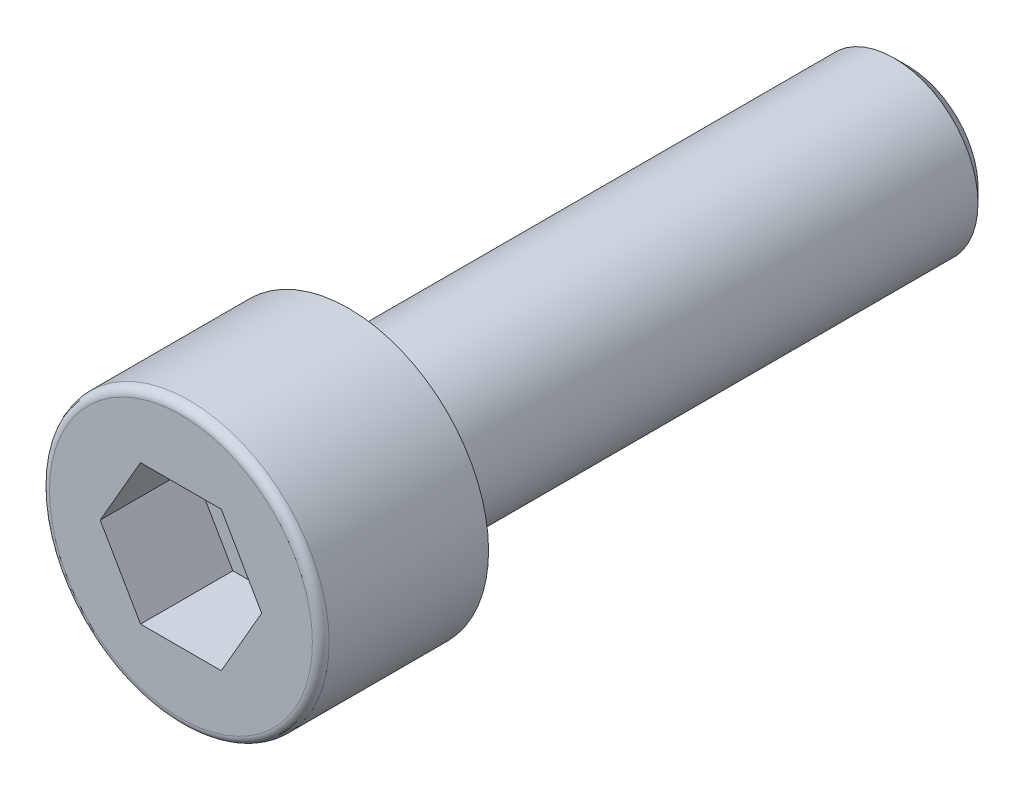
SolidWorks part; units mm, degrees
material "STAINLESS STEEL, 316S16"
ref_plane "Front Plane" through (0, 0, 0) normal (0, 0, 1) x (1, 0, 0)
ref_plane "Top Plane" through (0, 0, 0) normal (0, 1, 0) x (1, 0, 0)
ref_plane "Right Plane" through (0, 0, 0) normal (1, 0, 0) x (0, 0, -1)
sketch "Sketch1" plane through (0, 0, 0) normal (0, -1, 0) x (1, 0, 0)
  line L0 (0, 6) -> (0, -20) construction
  line L1 (0, -20) -> (-3, -20)
  line L2 (-3, -20) -> (-3, 0)
  line L3 (-3, 0) -> (-5, 0)
  line L4 (-5, 0) -> (-5, 5.7)
  line L5 (-4.7, 6) -> (0, 6)
  line L6 (0, 6) -> (0, -20)
  arc A0 (-5, 5.7) -> (-4.7, 6) centre (-4.7, 5.7) cw
  dimension "D4" = 0.3
  dimension "D1" = 6
  dimension "D2" = 10
  dimension "D3" = 6
  dimension "L" = 20
revolve "Revolve1" add sketch "Sketch1" angle 360 mid plane about L0
cosmetic thread "Thread" parameters "D1"=18, "D2"=4.891
sketch "Sketch2" plane through (0, 0, 6) normal (0, 0, 1) x (1, 0, 0)
  line L1 (2.8868, 0) -> (1.4434, 2.5)
  line L2 (1.4434, 2.5) -> (-1.4434, 2.5)
  line L3 (-1.4434, 2.5) -> (-2.8868, 0)
  line L4 (-2.8868, 0) -> (-1.4434, -2.5)
  line L5 (-1.4434, -2.5) -> (1.4434, -2.5)
  line L6 (1.4434, -2.5) -> (2.8868, 0)
  circle A0 centre (0, 0) radius 2.5 construction
  dimension "D1" = 5
extrude "Cut-Extrude1" cut sketch "Sketch2" against normal blind 3.3
chamfer "Chamfer1" distance 0.5 angle 45 1 edges at (3, 0, -20)
equation "\"D4@Sketch1\" = (\"D1@Sketch1\"/2)/10"
